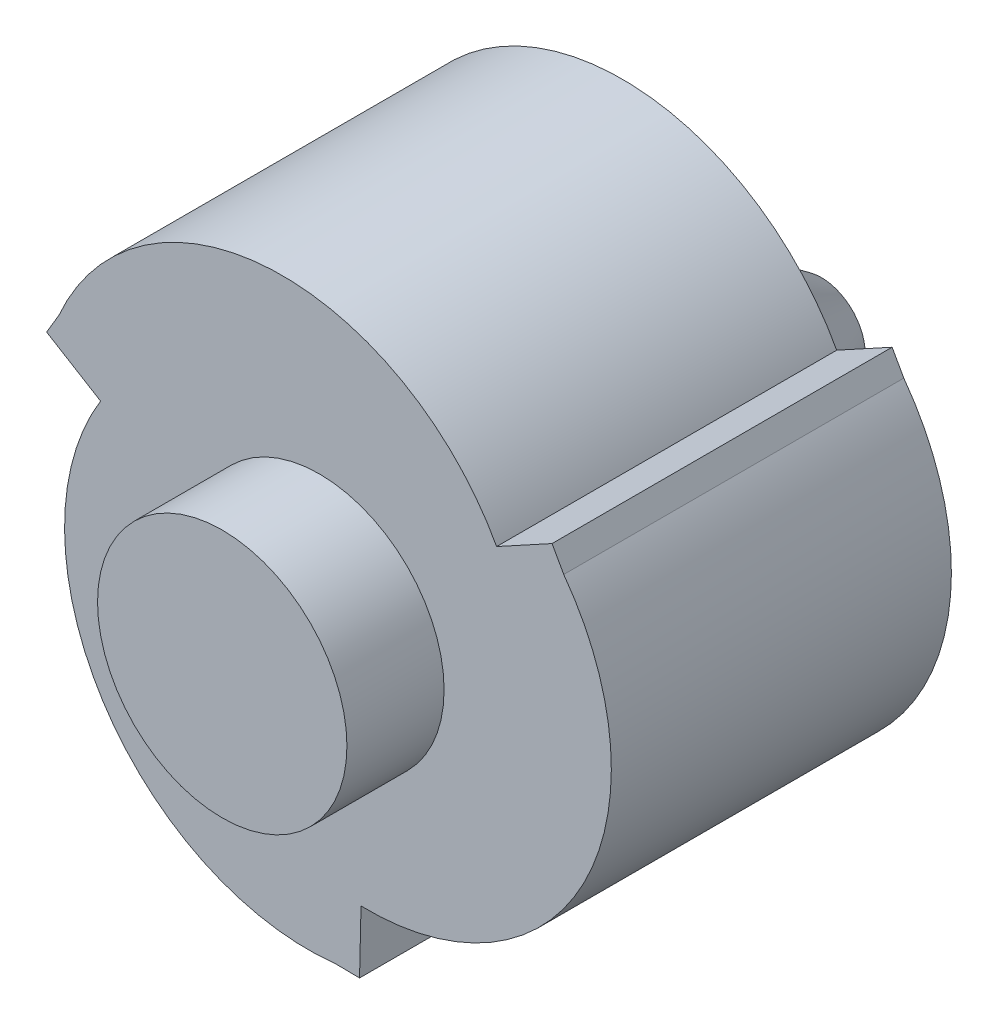
SolidWorks part; units mm, degrees
ref_plane "Alzado" through (0, 0, 0) normal (0, 0, 1) x (1, 0, 0)
ref_plane "Planta" through (0, 0, 0) normal (0, 1, 0) x (1, 0, 0)
ref_plane "Vista lateral" through (0, 0, 0) normal (1, 0, 0) x (0, 0, -1)
sketch "Croquis1" plane through (0, 0, 0) normal (0, 0, 1) x (1, 0, 0)
  line L0 (-54.5351, 31.4828) -> (-55.2579, 32.775)
  line L1 (-69.6242, 5.1176) -> (-68.6242, 5.1176)
  line L2 (-68.6242, 5.1176) -> (-68.6242, 9.1176)
  line L3 (-85.7122, 29.7526) -> (-86.47, 28.4805)
  line L4 (-83.9136, 29.8676) -> (-84.4136, 29.0016)
  line L5 (-84.4136, 29.0016) -> (-80.9495, 27.0016)
  line L6 (-86.47, 28.4805) -> (-83.1384, 26.453)
  line L7 (-55.3348, 29.8676) -> (-55.8348, 30.7337)
  line L8 (-55.8348, 30.7337) -> (-59.2989, 28.7337)
  line L9 (-55.2579, 32.775) -> (-58.6796, 30.9036)
  line L10 (-68.6253, 3.6175) -> (-67.1448, 3.5974)
  line L11 (-67.1448, 3.5974) -> (-67.0547, 7.4963)
  arc A1 (-69.6242, 5.1176) -> (-80.9495, 27.0016) centre (-70.3006, 18.6401) cw
  arc A2 (-55.3348, 29.8676) -> (-68.6242, 9.1176) centre (-66.7074, 22.5206) cw
  arc A3 (-83.9136, 29.8676) -> (-59.2989, 28.7337) centre (-71.8646, 23.6922) cw
  arc A4 (-83.1384, 26.453) -> (-68.6253, 3.6175) centre (-70.3045, 18.58) ccw
  arc A5 (-58.6796, 30.9036) -> (-85.7122, 29.7526) centre (-71.9148, 23.7256) ccw
  arc A6 (-67.0547, 7.4963) -> (-54.5351, 31.4828) centre (-66.6534, 22.5474) ccw
  point P16 (-69.6242, 21.6176)
  point P24 (-69.6242, 21.6176)
  point P33 (-69.6242, 21.6176)
  dimension "D1" = 3
  dimension "D2" = 3
  dimension "D5" = 3
extrude "Saliente-Extruir1" add sketch "Croquis1" along normal blind 18
sketch "Croquis2" plane through (0, 0, 0) normal (0, 0, -1) x (-1, 0, 0)
  line L0 (67.0547, 7.4963) -> (67.1448, 3.5974)
  line L1 (67.1448, 3.5974) -> (68.6253, 3.6175)
  line L2 (58.6796, 30.9036) -> (55.2579, 32.775)
  line L3 (55.2579, 32.775) -> (54.5351, 31.4828)
  line L4 (83.1384, 26.453) -> (86.47, 28.4805)
  line L5 (86.47, 28.4805) -> (85.7122, 29.7526)
  arc A0 (68.6253, 3.6175) -> (83.1384, 26.453) centre (70.3045, 18.58) ccw
  arc A2 (54.5351, 31.4828) -> (67.0547, 7.4963) centre (66.6534, 22.5474) ccw
  arc A3 (85.7122, 29.7526) -> (58.6796, 30.9036) centre (71.9148, 23.7256) ccw
  circle A4 centre (69.6242, 21.6176) radius 2.7
  point P26 (69.6242, 21.6176)
  dimension "D1" = 3
extrude "Saliente-Extruir2" add sketch "Croquis2" along normal blind 1.5
sketch "Croquis3" plane through (0, 0, 18) normal (0, 0, 1) x (1, 0, 0)
  line L0 (-67.1448, 3.5974) -> (-67.0547, 7.4963)
  line L2 (-67.1448, 3.5974) -> (-68.6253, 3.6175)
  line L3 (-86.47, 28.4805) -> (-83.1384, 26.453)
  line L4 (-86.47, 28.4805) -> (-85.7122, 29.7526)
  line L5 (-55.2579, 32.775) -> (-58.6796, 30.9036)
  line L6 (-55.2579, 32.775) -> (-54.5351, 31.4828)
  arc A0 (-68.6253, 3.6175) -> (-83.1384, 26.453) centre (-70.3045, 18.58) cw
  arc A2 (-85.7122, 29.7526) -> (-58.6796, 30.9036) centre (-71.9148, 23.7256) cw
  arc A3 (-54.5351, 31.4828) -> (-67.0547, 7.4963) centre (-66.6534, 22.5474) cw
  dimension "D1" = 3
extrude "Saliente-Extruir3" add sketch "Croquis3" along normal blind 1.5
sketch "Croquis6" plane through (0, 0, -1.5) normal (0, 0, -1) x (-1, 0, 0)
  line L1 (72.3242, 21.6176) -> (66.9242, 21.6176)
  line L2 (72.3242, 21.6176) -> (72.3242, 20.4357)
  line L3 (72.3242, 20.4357) -> (66.9242, 20.4357)
  line L4 (66.9242, 21.6176) -> (66.9242, 20.4357)
  circle A0 centre (69.6242, 21.6176) radius 2.7 construction
extrude "Saliente-Extruir7" add sketch "Croquis6" along normal blind 10
ref_plane "Plano2" through (0, 21.6176, 0) normal (0, 1, 0) x (1, 0, 0)
sketch "Croquis7" plane through (0, 21.6176, 0) normal (0, 1, 0) x (1, 0, 0)
  line L1 (-72.3242, 11.5) -> (-66.9242, 11.5)
  line L2 (-72.3242, 11.5) -> (-72.3242, 1.5)
  line L3 (-72.3242, 1.5) -> (-66.9242, 1.5)
  line L4 (-66.9242, 11.5) -> (-66.9242, 1.5)
extrude "Cortar-Extruir2" cut sketch "Croquis7" against normal up to vertex (16.5 mm away)
sketch "Croquis8" plane through (0, 21.6176, 0) normal (0, 1, 0) x (1, 0, 0)
  line L0 (-72.3242, 1.5) -> (-79.4868, 1.5)
  line L1 (-72.3242, 1.5) -> (-72.3242, 11.5)
  line L2 (-79.4868, 1.5) -> (-72.3242, 11.5)
  line L6 (-72.3242, -19.5) -> (-69.6242, -19.5)
  line L7 (-69.6242, -19.5) -> (-69.6242, -25.5)
  line L8 (-69.6242, -25.5) -> (-72.3242, -25.5)
  line L9 (-77.3242, -25.5) -> (-77.3242, -19.5)
  line L10 (-72.3242, -25.5) -> (-77.3242, -25.5)
  line L11 (-77.3242, -19.5) -> (-72.3242, -19.5)
  dimension "D5" = 21
revolve "Revolución1" add sketch "Croquis8" angle 360 about L7
sketch "Croquis9" plane through (0, 21.6176, 0) normal (0, 1, 0) x (1, 0, 0)
  line L1 (-87.9437, -36.577) -> (-35.4756, -36.577)
  line L2 (-87.9437, -36.577) -> (-87.9437, 19.1063)
  line L3 (-87.9437, 19.1063) -> (-35.4756, 19.1063)
  line L4 (-35.4756, -36.577) -> (-35.4756, 19.1063)
